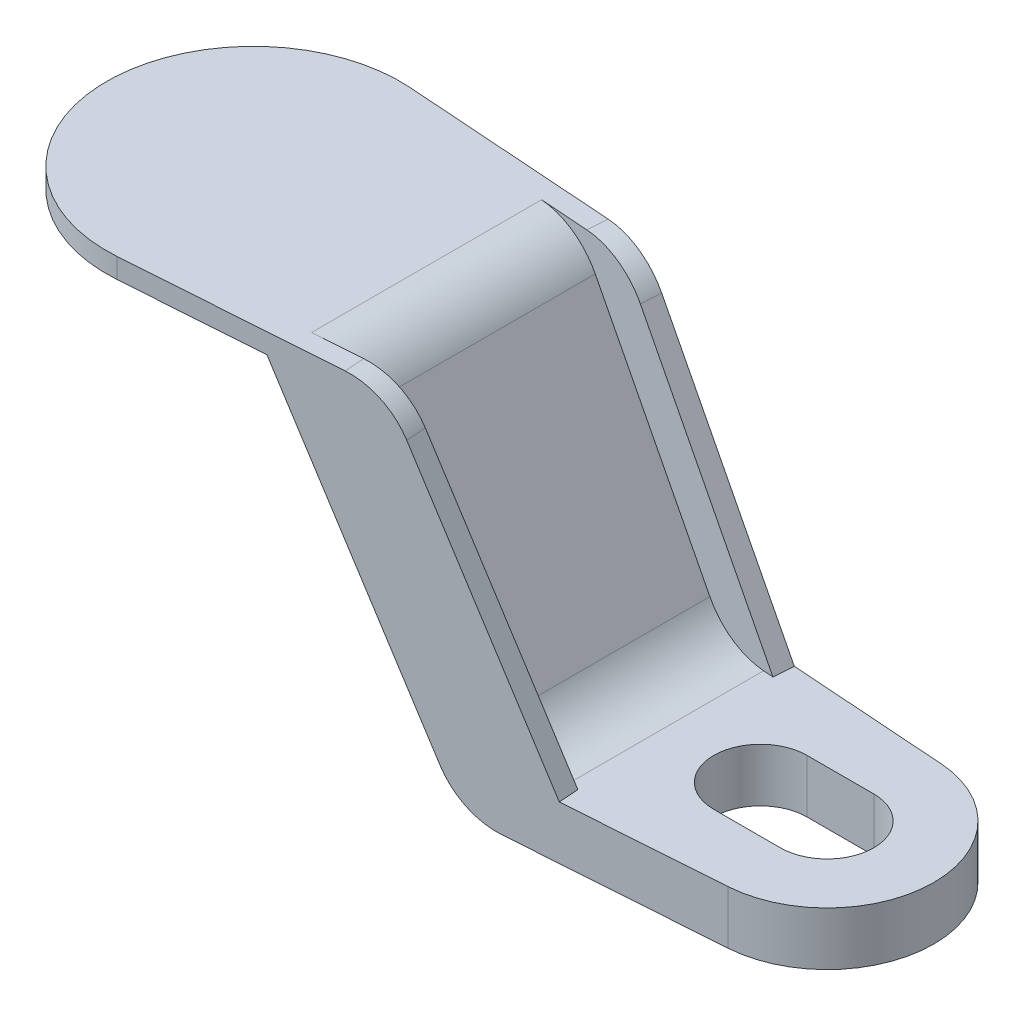
SolidWorks part; units mm, degrees
ref_plane "Plan de face" through (0, 0, 0) normal (0, 0, 1) x (1, 0, 0)
ref_plane "Plan de dessus" through (0, 0, 0) normal (0, 1, 0) x (1, 0, 0)
ref_plane "Plan de droite" through (0, 0, 0) normal (1, 0, 0) x (0, 0, -1)
sketch "Esquisse1" plane through (0, 0, 0) normal (0, 1, 0) x (1, 0, 0)
  line L0 (43, 0) -> (38, 0) construction
  line L1 (43, -3.5) -> (38, -3.5)
  line L2 (43, 3.5) -> (38, 3.5)
  line L3 (0.7674, 10.9732) -> (43.5581, 7.9805)
  line L4 (0.7674, -10.9732) -> (43.5581, -7.9805)
  arc A0 (0.7674, 10.9732) -> (0.7674, -10.9732) centre (0, 0) ccw
  arc A1 (43.5581, -7.9805) -> (43.5581, 7.9805) centre (43, 0) ccw
  arc A2 (43, -3.5) -> (43, 3.5) centre (43, 0) ccw
  arc A3 (38, 3.5) -> (38, -3.5) centre (38, 0) ccw
  point P5 (40.5, 0)
  dimension "D1" = 7
  dimension "D2" = 38
  dimension "D3" = 43
  dimension "D5" = 8
  dimension "D6" = 4.5
  dimension "D7" = 11
  dimension "D4" = 5
extrude "Boss.-Extru.1" add sketch "Esquisse1" along normal blind 25
sketch "Esquisse4" plane through (0, 0, 0) normal (0, 0, 1) x (1, 0, 0)
  line L0 (0.7674, 25) -> (-11, 25) construction
  line L1 (-11, 0) -> (28.5677, 0)
  line L2 (-11, 0) -> (-11, 23.5)
  line L3 (-11, 23.5) -> (15, 23.5)
  line L4 (28.5677, 0) -> (15, 23.5)
  line L5 (51, 25) -> (15.866, 25)
  line L6 (51, 25) -> (51, 4)
  line L7 (51, 4) -> (27.9904, 4)
  line L8 (15.866, 25) -> (27.9904, 4)
  line L9 (43.5581, 0) -> (51, 0) construction
  dimension "D1" = 15
  dimension "D2" = 1.5
  dimension "D3" = 4
  dimension "D4" = 23.0096
  dimension "D5" = 60
  dimension "D8" = 1.5
extrude "Enlèv. mat.-Extru.2" cut sketch "Esquisse4" against normal through all both and the other way through all
sketch "Esquisse6" plane through (0.7674, 0, 10.9732) normal (0.0698, 0, 0.9976) x (0.9976, 0, -0.0698)
  line L0 (0, 25) -> (15.1355, 25) construction
  line L1 (9.6457, 25) -> (18.8889, 25)
  line L2 (18.8889, 25) -> (16.0773, 23.3727) construction
  line L3 (24.1147, 0) -> (33.358, 0)
  line L5 (27.8682, 0) -> (42.8952, 0) construction
  line L6 (18.8889, 25) -> (33.358, 0)
  line L7 (27.2894, 4) -> (15.1355, 25) construction
  line L8 (9.6457, 25) -> (24.1147, 0)
  line L11 (14.2673, 23.5) -> (27.8682, 0) construction
  line L12 (14.7767, 22.62) -> (11.965, 20.9927) construction
  dimension "D1" = 8
extrude "Boss.-Extru.2" add sketch "Esquisse6" against normal blind 1.5
mirror "Symétrie1" about plane through (0, 0, 0) normal (0, 0, 1) of "Boss.-Extru.2"
fillet "Congé1" radius 5 8 edges at (28.5677, 0, 0) (15, 23.5, 0) (24.7711, 0, -8.5426) (24.7711, 0, 8.5426) (27.9904, 4, 0) (19.558, 25, 8.9072) (19.558, 25, -8.9072) (15.866, 25, 0)
